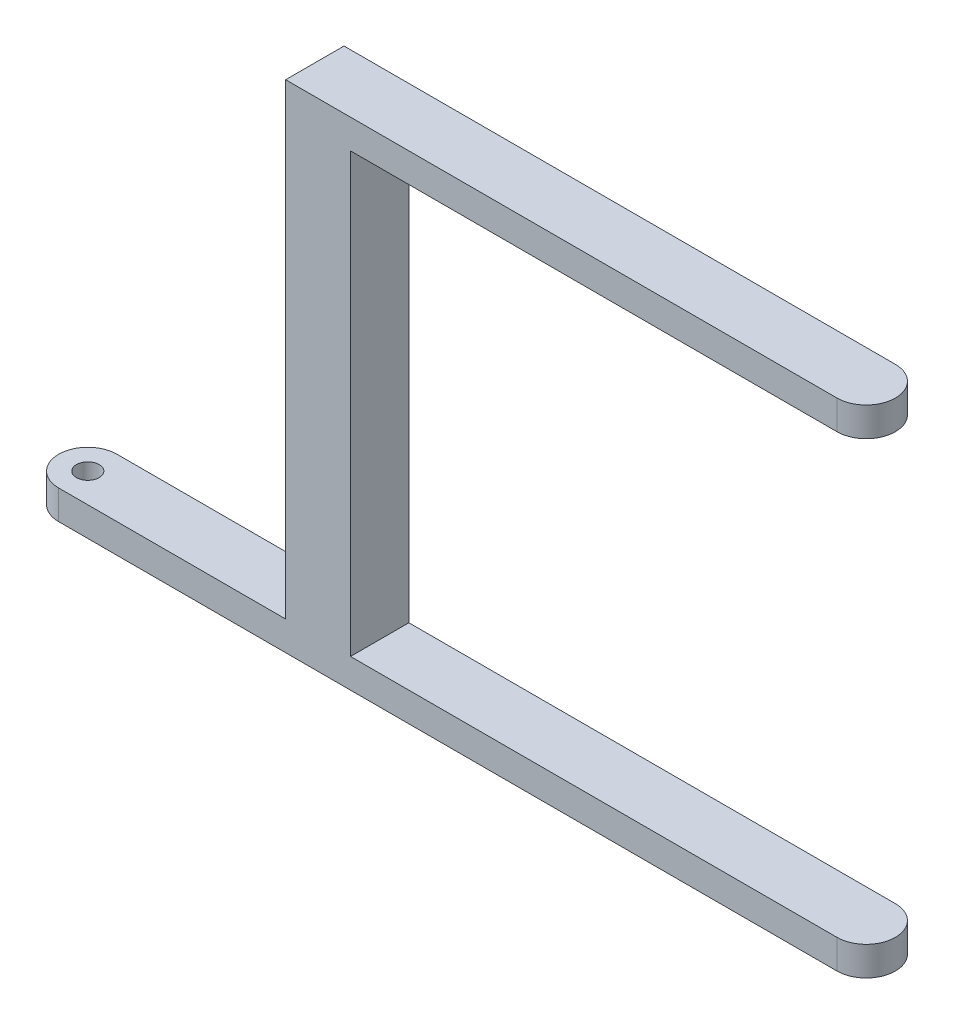
SolidWorks part; units mm, degrees
ref_plane "Front Plane" through (0, 0, 0) normal (0, 0, 1) x (1, 0, 0)
ref_plane "Top Plane" through (0, 0, 0) normal (0, 1, 0) x (1, 0, 0)
ref_plane "Right Plane" through (0, 0, 0) normal (1, 0, 0) x (0, 0, -1)
sketch "Sketch1" plane through (0, 0, 0) normal (0, 1, 0) x (1, 0, 0)
  line L0 (0, 0) -> (120, 0) construction
  line L1 (0, 4.5) -> (120, 4.5)
  line L2 (0, -4.5) -> (120, -4.5)
  arc A0 (0, 4.5) -> (0, -4.5) centre (0, 0) ccw
  arc A1 (120, -4.5) -> (120, 4.5) centre (120, 0) ccw
  point P3 (60, 0)
  dimension "D1" = 4.5
  dimension "D2" = 120
extrude "Boss-Extrude1" add sketch "Sketch1" along normal blind 4.5
sketch "Sketch2" plane through (0, 4.5, 0) normal (0, 1, 0) x (1, 0, 0)
  circle A0 centre (0, 0) radius 1.75
extrude "Cut-Extrude1" cut sketch "Sketch2" against normal blind 10
sketch "Sketch3" plane through (0, 4.5, 0) normal (0, 1, 0) x (1, 0, 0)
  line L0 (120, 4.5) -> (0, 4.5) construction
  line L1 (35, 4.5) -> (45, 4.5)
  line L2 (35, 4.5) -> (35, -4.5)
  line L3 (35, -4.5) -> (45, -4.5)
  line L4 (45, 4.5) -> (45, -4.5)
  line L5 (0, -4.5) -> (120, -4.5) construction
  arc A0 (0, 4.5) -> (0, -4.5) centre (0, 0) ccw construction
  dimension "D1" = 35
  dimension "D2" = 10
extrude "Boss-Extrude2" add sketch "Sketch3" along normal blind 67.5
sketch "Sketch4" plane through (0, 72, 0) normal (0, 1, 0) x (1, 0, 0)
  line L0 (45, -4.5) -> (120, -4.5) construction
  line L2 (35, 4.5) -> (35, -4.5)
  line L3 (35, -4.5) -> (118.25, -4.5)
  line L6 (35, -4.5) -> (120, -4.5)
  line L7 (35, -4.5) -> (35, 4.5)
  line L8 (35, 4.5) -> (120, 4.5)
  line L9 (120, -4.5) -> (120, 4.5)
  circle A2 centre (119.9601, 0) radius 4.5
  point P9 (120, 4.5)
  point P10 (120, -4.5)
  dimension "D1" = 9
  dimension "D2" = 84.9601
  dimension "D3" = 4.5
extrude "Boss-Extrude3" add sketch "Sketch4" along normal blind 4.5 contours L7 L6 L9 L8
sketch "Sketch5" plane through (0, 76.5, 0) normal (0, 1, 0) x (1, 0, 0)
  line L0 (120, -4.5) -> (120, 4.5) construction
  circle A0 centre (120, 0) radius 4.5
extrude "Boss-Extrude4" add sketch "Sketch5" against normal blind 4.5
